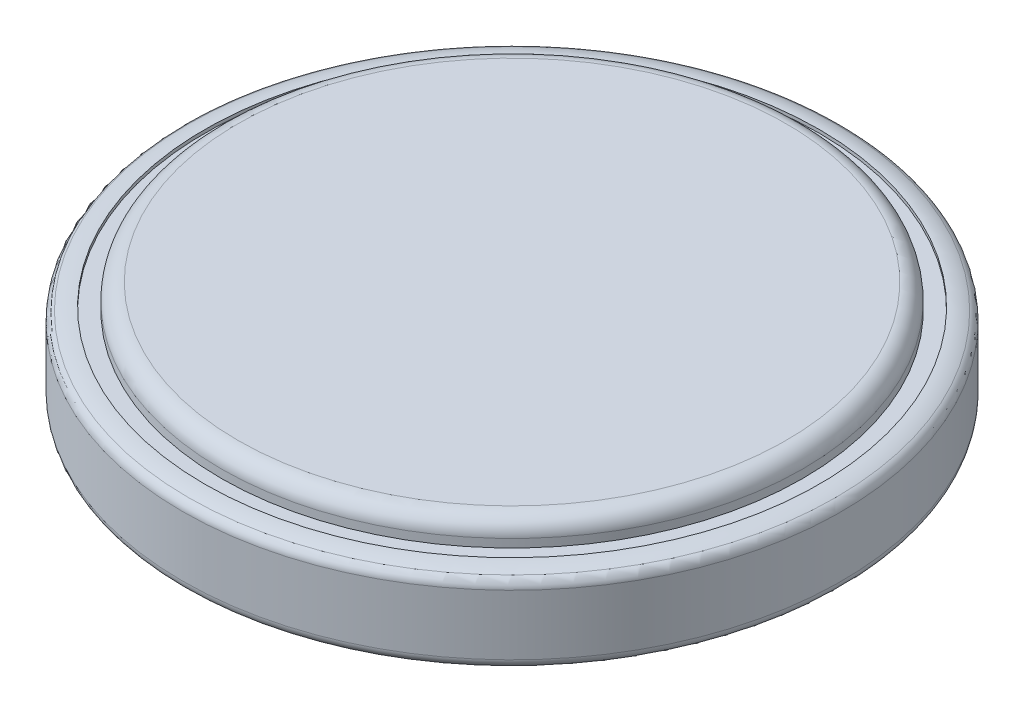
SolidWorks part; units mm, degrees
material "1060 Alloy"
ref_plane "Front" through (0, 0, 0) normal (0, 0, 1) x (1, 0, 0)
ref_plane "Top" through (0, 0, 0) normal (0, 1, 0) x (1, 0, 0)
ref_plane "Right" through (0, 0, 0) normal (1, 0, 0) x (0, 0, -1)
sketch "Sketch1" plane through (0, 0, 0) normal (0, 1, 0) x (1, 0, 0)
  circle A0 centre (0, 0) radius 9.975
  dimension "D1" = 19.95
extrude "Boss-Extrude1" add sketch "Sketch1" along normal blind 3.15
sketch "Sketch2" plane through (0, 0, 0) normal (0, 0, 1) x (1, 0, 0)
  line L0 (8.8, 3.15) -> (8.8, 2.5)
  line L1 (9.975, 3.15) -> (-9.975, 3.15) construction
  line L2 (8.8, 2.5) -> (9.3, 2.5)
  line L3 (0, 0) -> (0, 3.15) construction
  line L4 (9.975, 0) -> (9.975, 3.15) construction
  line L5 (-9.975, 0) -> (9.975, 0) construction
  line L6 (8.8, 3.15) -> (9.975, 3.15)
  line L7 (9.975, 3.15) -> (9.975, 2.3)
  arc A0 (9.3, 2.5) -> (9.975, 2.3) centre (9.3, 1.2609) cw
  dimension "D4" = 18.6
  dimension "D1" = 17.6
  dimension "D2" = 2.5
  dimension "D3" = 2.3
revolve "Cut-Revolve1" cut sketch "Sketch2" angle 360 about L3
fillet "Fillet1" radius 0.5 1 edges at (0, 3.15, -8.8)
sketch "Sketch3" plane through (0, 2.5, 0) normal (0, 1, 0) x (1, 0, 0)
  circle A0 centre (0, 0) radius 8.8 construction
  circle A1 centre (0, 0) radius 9.3
  circle A2 centre (0, 0) radius 9.3
  circle A3 centre (0, 0) radius 8.8
  dimension "D1" = 0
extrude "Cut-Extrude1" cut sketch "Sketch3" against normal blind 0.1
fillet "Fillet2" radius 0.3 2 edges at (0, 0, 9.975) (0, 2.3, -9.975)
